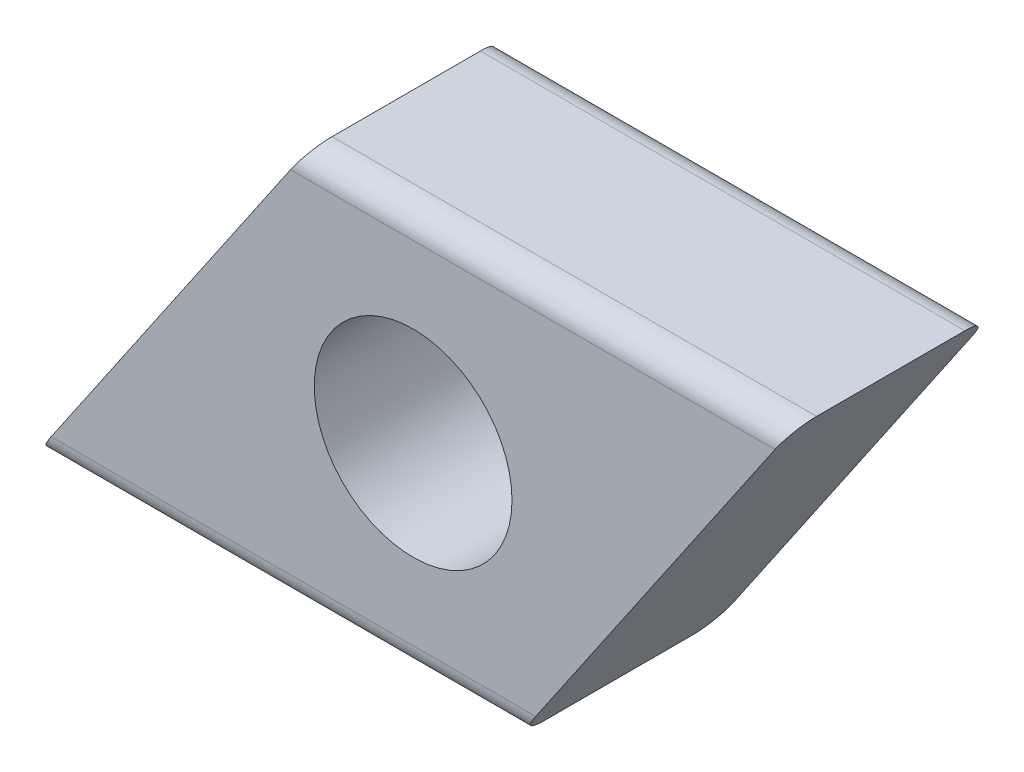
SolidWorks part; units mm, degrees
ref_plane "前视基准面" through (0, 0, 0) normal (0, 0, 1) x (1, 0, 0)
ref_plane "上视基准面" through (0, 0, 0) normal (0, 1, 0) x (1, 0, 0)
ref_plane "右视基准面" through (0, 0, 0) normal (1, 0, 0) x (0, 0, -1)
sketch "草图1" plane through (0, 0, 0) normal (0, 0, 1) x (1, 0, 0)
  line L0 (0, 0) -> (9.8, 0)
  line L1 (0, 0) -> (5.5219, 8.0962)
  line L2 (9.8, 0) -> (15.3219, 8.0962)
  line L3 (5.5219, 8.0962) -> (15.3219, 8.0962)
  dimension "D1" = 9.8
  dimension "D2" = 9.8
extrude "凸台-拉伸1" add sketch "草图1" along normal blind 4
sketch "草图2" plane through (0, 0, 4) normal (0, 0, 1) x (1, 0, 0)
  line L0 (12.5609, 4.0481) -> (2.7609, 4.0481) construction
  line L1 (9.8, 0) -> (15.3219, 8.0962) construction
  line L2 (5.5219, 8.0962) -> (0, 0) construction
  circle A0 centre (7.6609, 4.0481) radius 2
  dimension "D1" = 4
extrude "切除-拉伸1" cut sketch "草图2" against normal blind 4
sketch "草图3" plane through (0, 0, 4) normal (0, 0, 1) x (1, 0, 0)
  circle A0 centre (7.6609, 4.0481) radius 2 construction
  circle A1 centre (7.6609, 4.0481) radius 2
curve "螺旋线/涡状线1" pitch 1 height 4 turns 4
fillet "圆角1" radius 0.5 4 edges at (10.4219, 8.0962, 0) (10.4219, 8.0962, 4) (4.9, 0, 0) (4.9, 0, 4)
